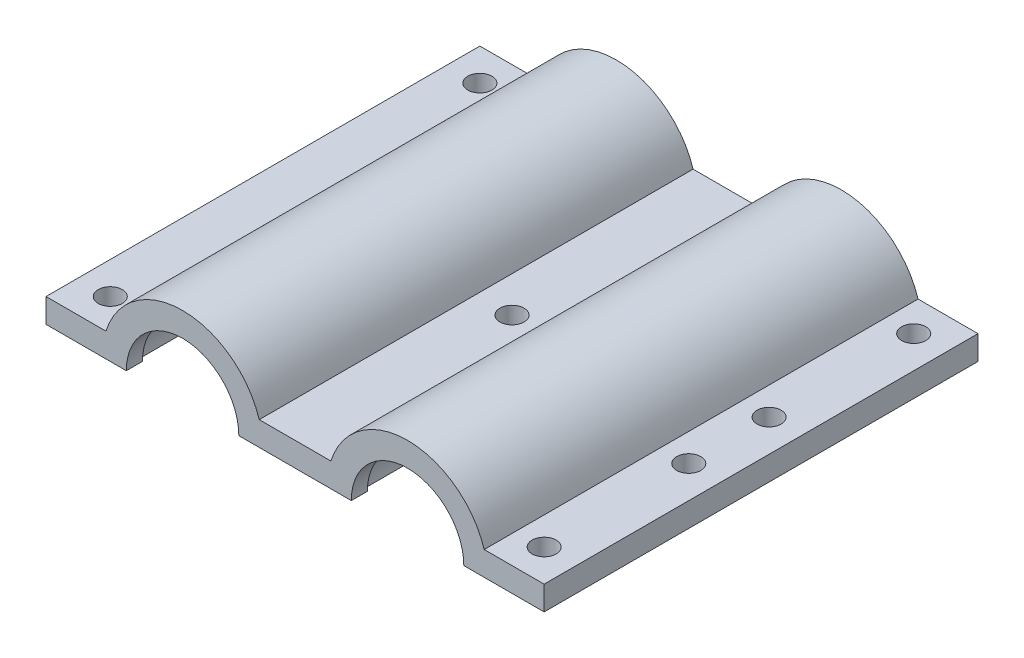
SolidWorks part; units mm, degrees
ref_plane "Front Plane" through (0, 0, 0) normal (0, 0, 1) x (1, 0, 0)
ref_plane "Top Plane" through (0, 0, 0) normal (0, 1, 0) x (1, 0, 0)
ref_plane "Right Plane" through (0, 0, 0) normal (1, 0, 0) x (0, 0, -1)
sketch "Sketch1" plane through (0, 0, 0) normal (0, 0, 1) x (1, 0, 0)
  line L0 (-31, 3) -> (-23.5394, 3)
  line L1 (-31, 0) -> (-21.5, 0)
  line L2 (-31, 0) -> (-31, 3)
  line L3 (-6.5, 0) -> (6.5, 0)
  line L4 (31, 0) -> (31, 3)
  line L5 (-4.4606, 3) -> (4.4606, 3)
  line L6 (23.5394, 3) -> (31, 3)
  line L7 (21.5, 0) -> (31, 0)
  arc A0 (-6.5, 0) -> (-21.5, 0) centre (-14, 0) ccw
  arc A1 (21.5, 0) -> (6.5, 0) centre (14, 0) ccw
  arc A2 (-4.4606, 3) -> (-23.5394, 3) centre (-14, 0) ccw
  arc A3 (23.5394, 3) -> (4.4606, 3) centre (14, 0) ccw
  dimension "D1" = 15
  dimension "D5" = 20
  dimension "D2" = 14
  dimension "D3" = 28
  dimension "D4" = 62
  dimension "D6" = 3
  dimension "D7" = 31
extrude "Boss-Extrude1" add sketch "Sketch1" along normal mid plane 54
sketch "Sketch2" plane through (0, 0, 27) normal (0, 0, 1) x (1, 0, 0)
  line L0 (-22, 0) -> (-21, 0)
  line L1 (-7, 0) -> (-6, 0)
  line L2 (21, 0) -> (22, 0)
  line L3 (6, 0) -> (7, 0)
  arc A0 (-6, 0) -> (-22, 0) centre (-14, 0) ccw
  arc A1 (-7, 0) -> (-21, 0) centre (-14, 0) ccw
  arc A2 (22, 0) -> (6, 0) centre (14, 0) ccw
  arc A3 (21, 0) -> (7, 0) centre (14, 0) ccw
  dimension "D1" = 16
  dimension "D2" = 16
  dimension "D3" = 14
extrude "Boss-Extrude2" add sketch "Sketch2" against normal blind 2
mirror "Mirror1" about plane through (0, 0, 0) normal (0, 0, 1) of "Boss-Extrude2"
sketch "Sketch3" plane through (0, 0, 0) normal (0, 0, 1) x (1, 0, 0)
  line L0 (-22, 0) -> (-21, 0)
  line L1 (6, 0) -> (7, 0)
  line L2 (-7, 0) -> (-6, 0)
  line L3 (21, 0) -> (22, 0)
  arc A0 (-6, 0) -> (-22, 0) centre (-14, 0) ccw
  arc A1 (-7, 0) -> (-21, 0) centre (-14, 0) ccw
  arc A2 (21, 0) -> (7, 0) centre (14, 0) ccw
  arc A3 (22, 0) -> (6, 0) centre (14, 0) ccw
  dimension "D1" = 16
  dimension "D2" = 14
extrude "Boss-Extrude3" add sketch "Sketch3" along normal mid plane 2
sketch "Sketch4" plane through (0, 3, 0) normal (0, 1, 0) x (1, 0, 0)
  line L0 (-23.5394, -27) -> (-31, -27) construction
  line L1 (-31, -27) -> (-31, 27) construction
  line L2 (-23.5394, 27) -> (-31, 27) construction
  line L3 (31, 27) -> (23.5394, 27) construction
  line L4 (31, -27) -> (31, 27) construction
  line L5 (31, -27) -> (23.5394, -27) construction
  circle A0 centre (-27, 23) radius 1.5
  circle A1 centre (-27, -23) radius 1.5
  circle A2 centre (27, -23) radius 1.5
  circle A3 centre (27, 23) radius 1.5
  circle A4 centre (0, 0) radius 1.5
  dimension "D1" = 3
  dimension "D2" = 4
  dimension "D3" = 4
  dimension "D4" = 4
  dimension "D5" = 4
  dimension "D6" = 4
  dimension "D7" = 4
  dimension "D8" = 4
  dimension "D9" = 4
extrude "Cut-Extrude1" cut sketch "Sketch4" against normal through all
sketch "Sketch5" plane through (0, 3, 0) normal (0, 1, 0) x (1, 0, 0)
  line L0 (31, -27) -> (31, 27) construction
  circle A0 centre (27, 5) radius 1.5
  circle A1 centre (27, -5) radius 1.5
  dimension "D1" = 3
  dimension "D2" = 4
  dimension "D3" = 10
  dimension "D4" = 5
  dimension "D5" = 4
extrude "Cut-Extrude2" cut sketch "Sketch5" against normal blind 10
